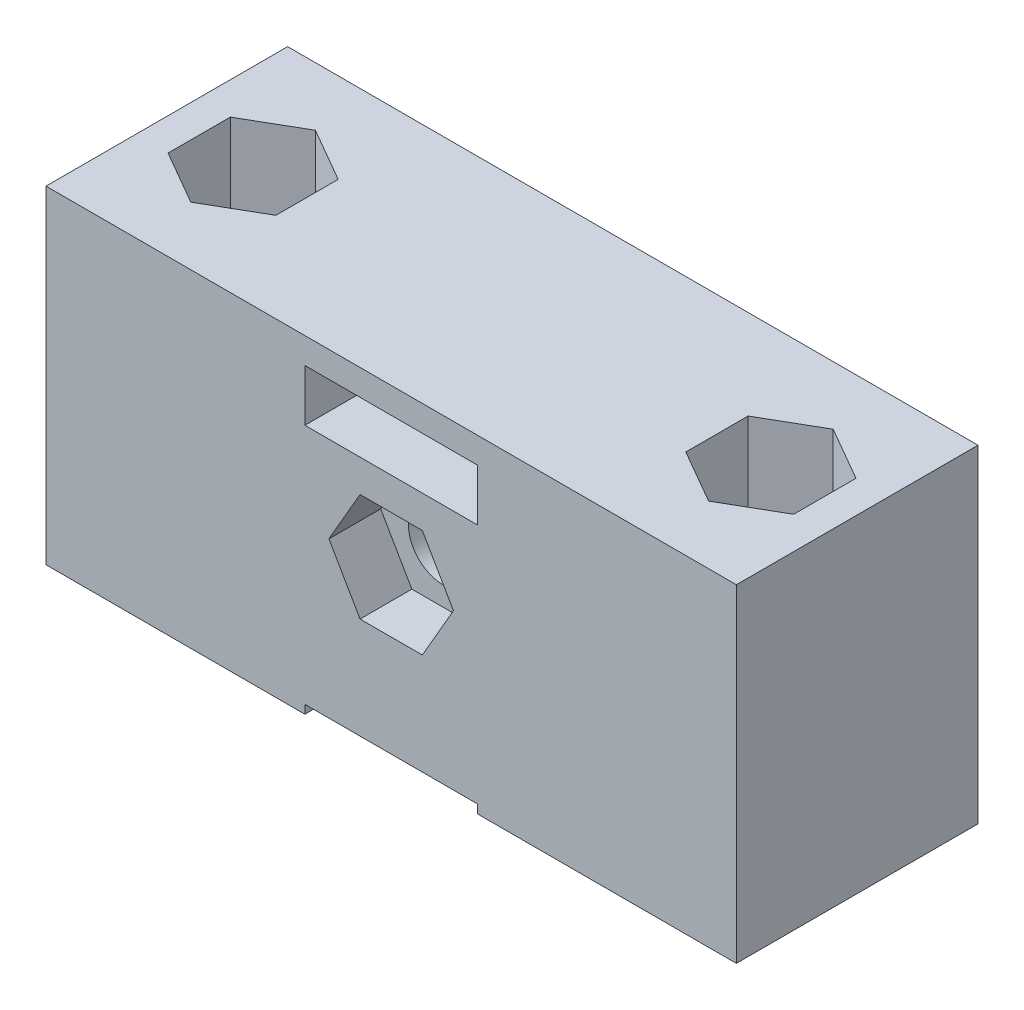
SolidWorks part; units mm, degrees
ref_plane "Front Plane" through (0, 0, 0) normal (0, 0, 1) x (1, 0, 0)
ref_plane "Top Plane" through (0, 0, 0) normal (0, 1, 0) x (1, 0, 0)
ref_plane "Right Plane" through (0, 0, 0) normal (1, 0, 0) x (0, 0, -1)
sketch "Sketch1" plane through (0, 0, 0) normal (0, 1, 0) x (1, 0, 0)
  line L1 (-20, 7) -> (20, 7)
  line L2 (-20, 7) -> (-20, -7)
  line L3 (-20, -7) -> (20, -7)
  line L4 (20, 7) -> (20, -7)
  line L5 (-20, 7) -> (20, -7) construction
  line L6 (-20, -7) -> (20, 7) construction
  point P0 (0, 0)
  dimension "D1" = 40
  dimension "D2" = 14
extrude "Boss-Extrude1" add sketch "Sketch1" along normal blind 19
sketch "Sketch2" plane through (0, 0, 7) normal (0, 0, 1) x (1, 0, 0)
  line L0 (0, 19) -> (0, 0) construction
  line L1 (-20, 19) -> (20, 19) construction
  line L3 (-5, 14.5) -> (5, 14.5)
  line L4 (-5, 14.5) -> (-5, 17.5)
  line L5 (-5, 17.5) -> (5, 17.5)
  line L6 (5, 14.5) -> (5, 17.5)
  line L7 (-5, 14.5) -> (5, 17.5) construction
  line L8 (-5, 17.5) -> (5, 14.5) construction
  line L9 (-5, -0.5) -> (5, -0.5)
  line L10 (-5, -0.5) -> (-5, 0.5)
  line L11 (-5, 0.5) -> (5, 0.5)
  line L12 (5, -0.5) -> (5, 0.5)
  line L13 (-5, -0.5) -> (5, 0.5) construction
  line L14 (-5, 0.5) -> (5, -0.5) construction
  point P5 (0, 16)
  dimension "D1" = 10
  dimension "D2" = 3
  dimension "D3" = 16
  dimension "D4" = 10
  dimension "D5" = 1
extrude "Cut-Extrude1" cut sketch "Sketch2" against normal blind 30
sketch "Sketch3" plane through (0, 0, 7) normal (0, 0, 1) x (1, 0, 0)
  line L0 (0, 19) -> (0, 0) construction
  line L1 (-20, 19) -> (20, 19) construction
  circle A0 centre (0, 9.5) radius 2
  dimension "D1" = 4
extrude "Cut-Extrude2" cut sketch "Sketch3" against normal through all
sketch "Sketch4" plane through (0, 19, 0) normal (0, 1, 0) x (1, 0, 0)
  line L0 (-20, 0) -> (20, 0) construction
  line L1 (-20, 7) -> (-20, -7) construction
  line L2 (20, -7) -> (20, 7) construction
  line L3 (0, 7) -> (0, -7) construction
  line L4 (20, 7) -> (-20, 7) construction
  line L5 (-20, -7) -> (20, -7) construction
  circle A0 centre (-15, 0) radius 1.6
  circle A1 centre (15, 0) radius 1.6
  dimension "D1" = 3.2
  dimension "D2" = 15
extrude "Cut-Extrude3" cut sketch "Sketch4" against normal through all
sketch "Sketch8" plane through (0, 0, 0) normal (0, -1, 0) x (-1, 0, 0)
  line L0 (-5, 7) -> (-5, -7) construction
  line L1 (5, -7) -> (-5, -7)
  line L2 (5, -7) -> (5, -6)
  line L3 (5, -6) -> (-5, -6)
  line L4 (-5, -7) -> (-5, -6)
  dimension "D1" = 1
extrude "Boss-Extrude2" [suppressed] add sketch "Sketch8" against normal up to next
sketch "Sketch9" plane through (0, 19, 0) normal (0, 1, 0) x (1, 0, 0)
  line L0 (0, 7) -> (0, -7) construction
  line L1 (-15, 3.6084) -> (-18.125, 1.8042)
  line L2 (-18.125, 1.8042) -> (-18.125, -1.8042)
  line L3 (-18.125, -1.8042) -> (-15, -3.6084)
  line L4 (-15, -3.6084) -> (-11.875, -1.8042)
  line L5 (-11.875, -1.8042) -> (-11.875, 1.8042)
  line L6 (-11.875, 1.8042) -> (-15, 3.6084)
  line L7 (20, 7) -> (-20, 7) construction
  line L8 (-20, -7) -> (20, -7) construction
  line L9 (11.875, 1.8042) -> (15, 3.6084)
  line L10 (11.875, -1.8042) -> (11.875, 1.8042)
  line L11 (15, -3.6084) -> (11.875, -1.8042)
  line L12 (18.125, -1.8042) -> (15, -3.6084)
  line L13 (18.125, 1.8042) -> (18.125, -1.8042)
  line L14 (15, 3.6084) -> (18.125, 1.8042)
  circle A0 centre (-15, 0) radius 3.125 construction
  circle A1 centre (15, 0) radius 3.125 construction
  dimension "D1" = 6.25
extrude "Cut-Extrude4" cut sketch "Sketch9" against normal blind 10
sketch "Sketch10" plane through (0, 0, 7) normal (0, 0, 1) x (1, 0, 0)
  line L1 (1.8042, 12.625) -> (-1.8042, 12.625)
  line L2 (-1.8042, 12.625) -> (-3.6084, 9.5)
  line L3 (-3.6084, 9.5) -> (-1.8042, 6.375)
  line L4 (-1.8042, 6.375) -> (1.8042, 6.375)
  line L5 (1.8042, 6.375) -> (3.6084, 9.5)
  line L6 (3.6084, 9.5) -> (1.8042, 12.625)
  circle A0 centre (0, 9.5) radius 3.125 construction
  dimension "D1" = 6.25
extrude "Cut-Extrude5" cut sketch "Sketch10" against normal blind 3
equation "\"X-ROD-SPACING\"=45"
equation "\"Y-ROD-SPACING\"=75"
equation "\"Z-ROD-SPACING\"=17.5"
equation "\"Y-BED-OFFSET\"=2"
equation "\"Y-BED-ROD-INSET\"=3.5"
equation "\"Y-BED-SCREW-SPACING\"=209"
equation "\"Y-BED-SCREW-CUTOUT-SLOT-HEIGHT\"=2"
equation "\"T-SLOT-NUT-FILLET-RADIUS\"=0.5"
equation "\"T-SLOT-SCREW-SHAFT-RADIUS\"=1.55"
equation "\"T-SLOT-SCREW-SHAFT-CUTOUT-LENGTH\"=11.0"
equation "\"T-SLOT-NUT-DEPTH\"=3.5"
equation "\"T-SLOT-NUT-WIDTH\"=2.85"
equation "\"T-SLOT-NUT-END-DISTANCE\"=8"
equation "\"ACRYLIC-THICKNESS\"=10"
equation "\"ACRYLIC-THICKNESS2\"=4.5"
equation "\"ACRYLIC-TAB-CUTOUT-SIZE\"=\"ACRYLIC-THICKNESS\"+\"ACRYLIC-TAB-TOLERANCE\"*2"
equation "\"ACRYLIC-TAB-TOLERANCE\"=-.05"
equation "\"ACRYLIC-TAB-WIDTH\"=\"ACRYLIC-THICKNESS\""
equation "\"ACRYLIC-M3-HOLE\"=2.9"
equation "\"SMOOTHROD-CAP-SCREW-DISTANCE\"=20"
equation "\"FRAME-WIDTH-INNER\"=370"
equation "\"NEMA17-HOLE-SPACING\"=31"
equation "\"NEMA17-CENTRAL-CUTOUT\"=22.5"
equation "\"Z-BRACKET-REACH\"=55"
equation "\"Z-ROD-INSET\"=16"
equation "\"TOP-BRACKET-SPACING\"=40"
equation "\"SMOOTHROD-X-LENGTH\"=350"
equation "\"SMOOTHROD-Y-LENGTH\"=350"
equation "\"SMOOTHROD-Z-LENGTH\"=350"
equation "\"SMOOTHROD-TIGHTENING-HEADROOM\"=.25"
equation "\"LEADSCREW-Z-LENGTH\"=300"
equation "\"SCREW-LENGTH-FRAME\"=\"ACRYLIC-THICKNESS\" + 10"
equation "\"SCREW-LENGTH-MOTOR\"=\"ACRYLIC-THICKNESS\" + 5"
equation "\"SCREW-LENGTH-EXTRUDER\"=28"
equation "\"SCREW-HEAD-RADIUS\"=6"
equation "\"PRINTED-M3-HOLE\"=3.5"
equation "\"PRINTED-X-SMOOTHROD-DIAMETER\"=9.0"
equation "\"PRINTED-X-SMOOTHROD-CUTOUT\"=10"
equation "\"PRINTED-X-BASE-HEIGHT\"=10"
equation "\"PRINTED-LM8UU-CUTOUT-SIZE\"=15.5"
equation "\"PRINTED-LM8UU-CUTOUT-LENGTH\"=24.5"
equation "\"PRINTED-X-IDLER-HEIGHT\"=16"
equation "\"PSU-MOUNTING-WIDTH\"=95"
equation "\"PSU-MOUNTING-HEIGHT\"=177"
equation "\"Y-BELT-TO-ROD-DISTANCE\"=20"
equation "\"SPOOL-HOLDER-ROD-SPACING\"=150"
equation "\"ACRYLIC-X-CARRIAGE-WIDTH\"=55"
equation "\"ACRYLIC-X-CARRIAGE-HEIGHT\"=75"
equation "\"ACRYLIC-X-CARRIAGE-LM8UU-CUTOUT-WIDTH\"=24.25"
equation "\"ACRYLIC-X-CARRIAGE-LM8UU-CUTOUT-HEIGHT\"=11.0"
equation "\"ACRYLIC-X-CARRIAGE-SCREW-SPACING-X\"=15"
equation "\"ACRYLIC-X-CARRIAGE-SCREW-SPACING-Y\"=33"
equation "\"ACRYLIC-X-CARRIAGE-CENTER-TAB-SPACING\"=14"
equation "\"ACRYLIC-X-CARRIAGE-EXTRUDER-OFFSET\"=26"
equation "\"ACRYLIC-X-CARRIAGE-EXTRUDER-ANGLE\"=90"
equation "\"ACRYLIC-X-CARRIAGE-EXTRUDER-SHELF-DEPTH\"=\"ACRYLIC-X-CARRIAGE-EXTRUDER-OFFSET\" + 28"
equation "\"ACRYLIC-X-CARRIAGE-EXTRUDER-BRACE-SPACING\"=23"
equation "\"ACRYLIC-X-CARRIAGE-EXTRUDER-BRACE-TAB-OFFSET\"=20"
equation "\"ACRYLIC-X-CARRIAGE-EXTRUDER-BRACE-HEIGHT\"=35"
equation "\"ACRYLIC-X-CARRIAGE-EXTRUDER-BRACE-SCREW-SPACING\"=22"
equation "\"ACRYLIC-X-CARRIAGE-DUAL-WIDTH-MULTIPLIER\"=1.65"
equation "\"ACRYLIC-X-CARRIAGE-DUAL-HOTEND-SPACING\"=42"
equation "\"ACRYLIC-X-CARRIAGE-DUAL-WIDTH\"=75"
equation "\"ACRYLIC-X-CARRIAGE-DUAL-HOTEND-SEPARATION\"=36"
equation "\"ACRYLIC-X-CARRIAGE-DUAL-MOUNT-PLATE-DEPTH\"=75"
equation "\"ACRYLIC-X-CARRIAGE-DUAL-MOUNT-BRACE-WIDTH\"=33"
equation "\"ACRYLIC-X-CARRIAGE-DUAL-MOUNT-SCREW-WIDTH\"=40"
equation "\"BLOWER-FAN-WIDTH\"=15"
equation "\"PRINTED-M3-NUT-AF\"=6.25"
equation "\"D1@Sketch9\"=\"PRINTED-M3-NUT-AF\""
equation "\"D1@Sketch10\"=\"PRINTED-M3-NUT-AF\""
